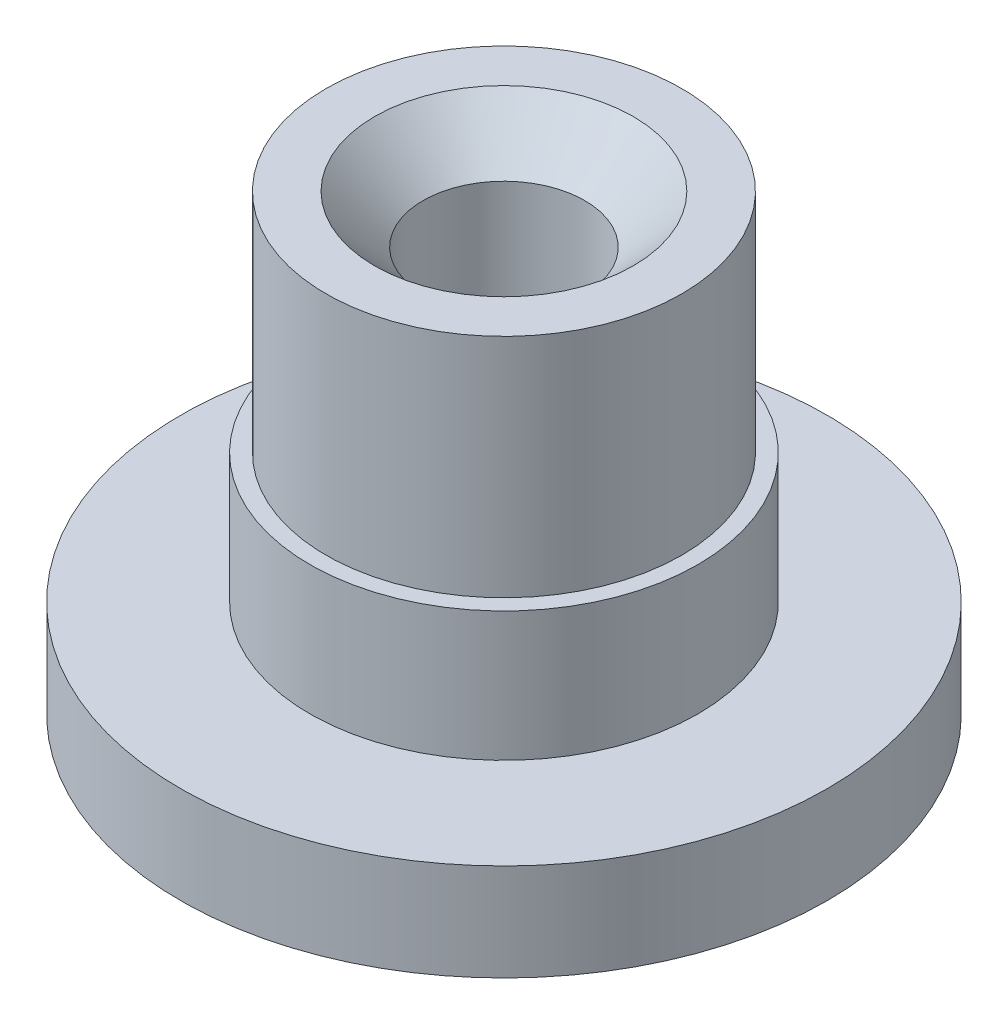
SolidWorks part; units mm, degrees
ref_plane "Front Plane" through (0, 0, 0) normal (0, 0, 1) x (1, 0, 0)
ref_plane "Top Plane" through (0, 0, 0) normal (0, 1, 0) x (1, 0, 0)
ref_plane "Right Plane" through (0, 0, 0) normal (1, 0, 0) x (0, 0, -1)
sketch "Sketch1" plane through (0, 0, 0) normal (0, 0, 1) x (1, 0, 0)
  line L1 (10, 0) -> (10, 3)
  line L2 (10, 3) -> (6, 3)
  line L3 (6, 3) -> (6, 7)
  line L4 (6, 7) -> (5.5, 7)
  line L5 (5.5, 7) -> (5.5, 14)
  line L6 (5.5, 14) -> (4, 14)
  line L7 (4, 14) -> (2.5, 12.5)
  line L8 (2.5, 12.5) -> (2.5, 0)
  line L9 (2.5, 0) -> (10, 0)
  line L10 (0, -1000) -> (0, 49000) construction
  dimension "D1" = 10
  dimension "D2" = 6
  dimension "D3" = 2.5
  dimension "D4" = 4
  dimension "D5" = 45
  dimension "D6" = 5.5
  dimension "D7" = 14
  dimension "D8" = 7
  dimension "D9" = 4
revolve "Revolve1" add sketch "Sketch1" angle 360 about L10
